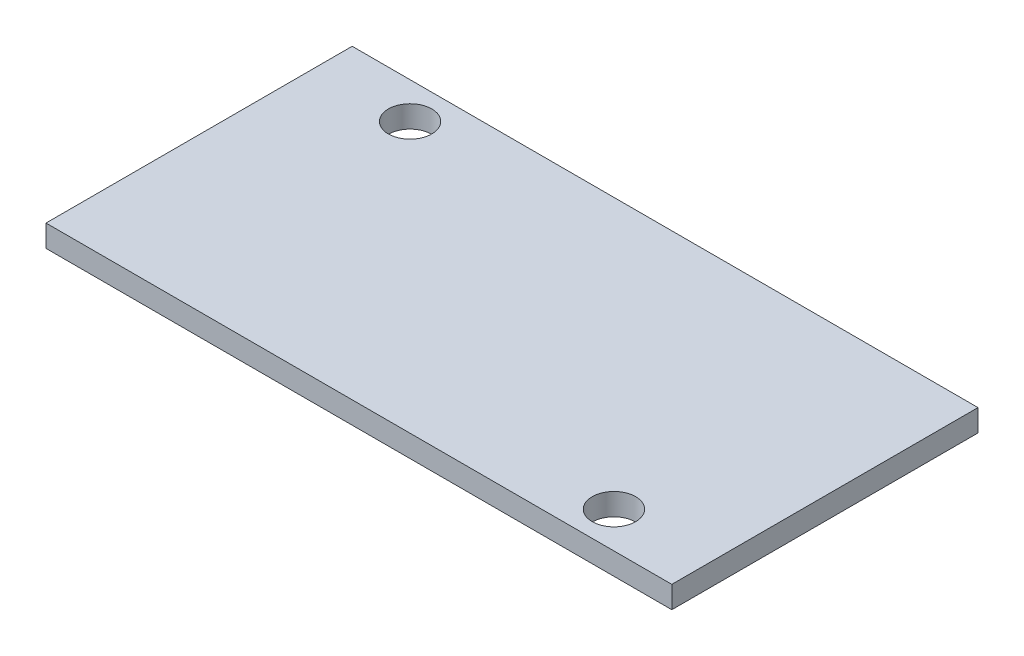
SolidWorks part; units mm, degrees
ref_plane "Front Plane" through (0, 0, 0) normal (0, 0, 1) x (1, 0, 0)
ref_plane "Top Plane" through (0, 0, 0) normal (0, 1, 0) x (1, 0, 0)
ref_plane "Right Plane" through (0, 0, 0) normal (1, 0, 0) x (0, 0, -1)
sketch "Sketch1" plane through (0, 0, 0) normal (0, 1, 0) x (1, 0, 0)
  line L1 (-21.625, -10.58) -> (21.625, -10.58)
  line L2 (-21.625, -10.58) -> (-21.625, 10.58)
  line L3 (-21.625, 10.58) -> (21.625, 10.58)
  line L4 (21.625, -10.58) -> (21.625, 10.58)
  line L5 (-21.625, -10.58) -> (21.625, 10.58) construction
  line L6 (-21.625, 10.58) -> (21.625, -10.58) construction
  point P0 (0, 0)
  dimension "D1" = 21.16
  dimension "D2" = 43.25
extrude "Boss-Extrude1" add sketch "Sketch1" along normal blind 1.52
sketch "Sketch2" plane through (0, 1.52, 0) normal (0, 1, 0) x (1, 0, 0)
  line L0 (-21.625, 10.58) -> (-21.625, -10.58) construction
  line L1 (21.625, -10.58) -> (21.625, 10.58) construction
  line L2 (-21.625, -10.58) -> (21.625, -10.58) construction
  line L3 (21.625, 10.58) -> (-21.625, 10.58) construction
  circle A0 centre (-15.125, 8.08) radius 1.5
  circle A1 centre (15.125, -8.08) radius 1.5
  dimension "D5" = 3
  dimension "D1" = 6.5
  dimension "D2" = 6.5
  dimension "D3" = 2.5
  dimension "D4" = 2.5
extrude "Cut-Extrude1" cut sketch "Sketch2" against normal through all
